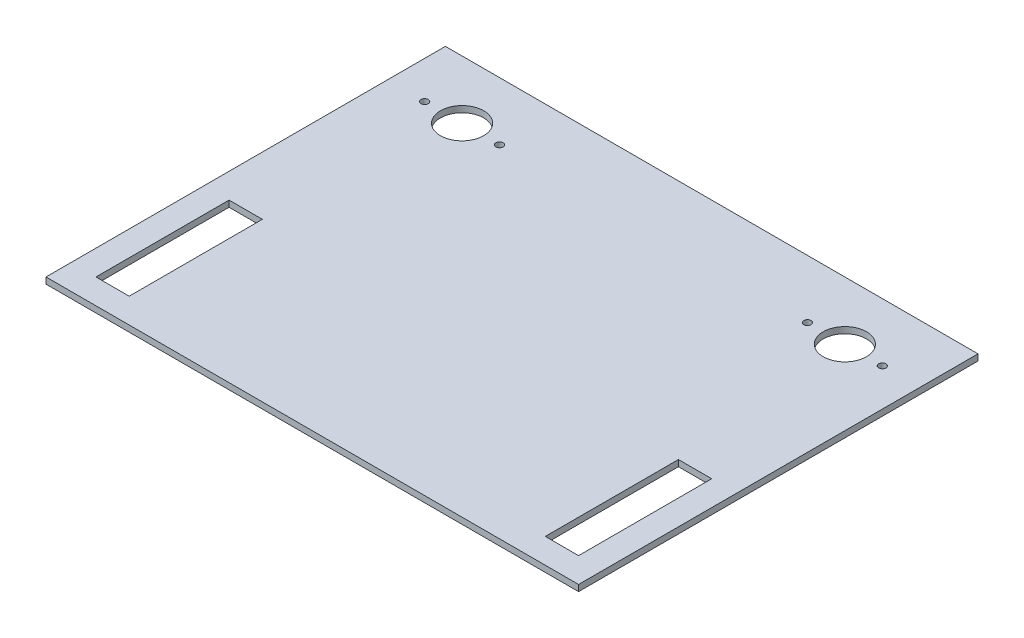
SolidWorks part; units mm, degrees
material "6061-T6 (SS)"
ref_plane "Front Plane" through (0, 0, 0) normal (0, 0, 1) x (1, 0, 0)
ref_plane "Top Plane" through (0, 0, 0) normal (0, 1, 0) x (1, 0, 0)
ref_plane "Right Plane" through (0, 0, 0) normal (1, 0, 0) x (0, 0, -1)
sketch "Sketch1" plane through (0, 0, 0) normal (0, 1, 0) x (1, 0, 0)
  line L1 (0, 0) -> (406.4, 0)
  line L2 (0, 0) -> (0, 304.8)
  line L3 (0, 304.8) -> (406.4, 304.8)
  line L4 (406.4, 0) -> (406.4, 304.8)
  dimension "D1" = 406.4
  dimension "D2" = 304.8
extrude "Boss-Extrude1" add sketch "Sketch1" along normal blind 4.7625
sketch "Sketch2" plane through (0, 4.7625, 0) normal (0, 1, 0) x (1, 0, 0)
  line L0 (0, 304.8) -> (0, 0) construction
  line L1 (19.05, 19.05) -> (44.45, 19.05)
  line L2 (19.05, 19.05) -> (19.05, 120.65)
  line L3 (19.05, 120.65) -> (44.45, 120.65)
  line L4 (44.45, 19.05) -> (44.45, 120.65)
  line L5 (0, 0) -> (406.4, 0) construction
  line L6 (203.2, 304.8) -> (203.2, 0) construction
  line L7 (406.4, 304.8) -> (0, 304.8) construction
  line L8 (387.35, 120.65) -> (361.95, 120.65)
  line L9 (361.95, 19.05) -> (361.95, 120.65)
  line L10 (387.35, 19.05) -> (361.95, 19.05)
  line L11 (387.35, 19.05) -> (387.35, 120.65)
  line L12 (73.66, 260.35) -> (82.9469, 260.35) construction
  line L13 (40.64, 260.35) -> (31.3531, 260.35) construction
  line L14 (365.76, 260.35) -> (375.0469, 260.35) construction
  line L15 (332.74, 260.35) -> (323.4531, 260.35) construction
  circle A0 centre (57.15, 260.35) radius 16.51
  circle A1 centre (85.725, 260.35) radius 2.7781
  circle A2 centre (28.575, 260.35) radius 2.7781
  circle A3 centre (377.825, 260.35) radius 2.7781
  circle A4 centre (320.675, 260.35) radius 2.7781
  circle A5 centre (349.25, 260.35) radius 16.51
  dimension "D5" = 33.02
  dimension "D6" = 5.5562
  dimension "D7" = 28.575
  dimension "D1" = 25.4
  dimension "D2" = 101.6
  dimension "D3" = 19.05
  dimension "D4" = 19.05
  dimension "D8" = 44.45
  dimension "D9" = 57.15
extrude "Cut-Extrude1" cut sketch "Sketch2" against normal blind 6.35
